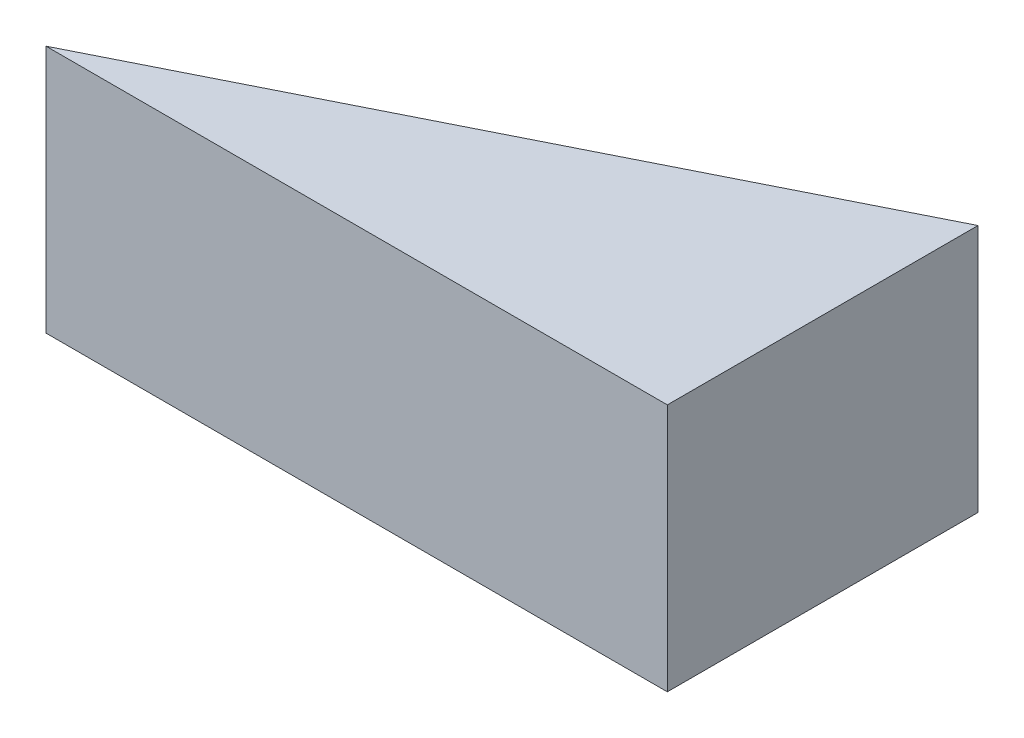
SolidWorks part; units mm, degrees
ref_plane "Front Plane" through (0, 0, 0) normal (0, 0, 1) x (1, 0, 0)
ref_plane "Top Plane" through (0, 0, 0) normal (0, 1, 0) x (1, 0, 0)
ref_plane "Right Plane" through (0, 0, 0) normal (1, 0, 0) x (0, 0, -1)
sketch "Sketch1" plane through (0, 0, 0) normal (0, 1, 0) x (1, 0, 0)
  line L0 (0, 10) -> (0, 0)
  line L1 (0, 0) -> (-20, 0)
  line L2 (-20, 0) -> (0, 10)
  dimension "D1" = 20
  dimension "D2" = 10
extrude "Boss-Extrude1" add sketch "Sketch1" along normal blind 8
